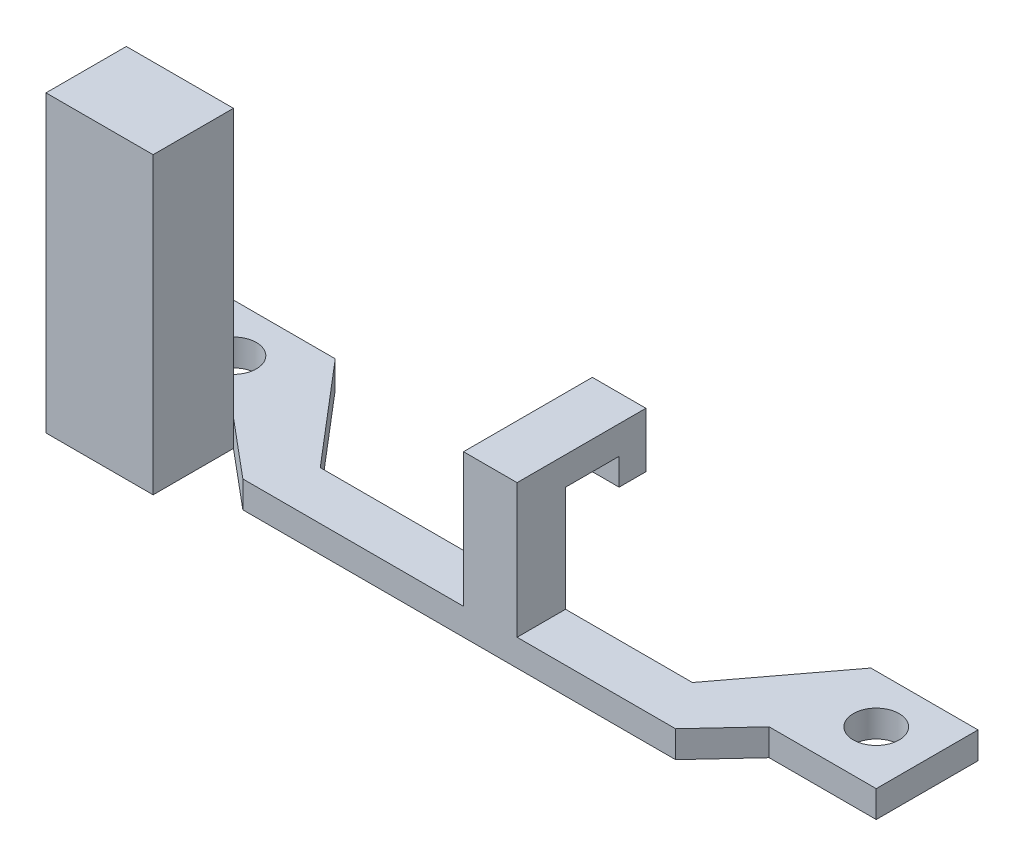
SolidWorks part; units mm, degrees
ref_plane "Front Plane" through (0, 0, 0) normal (0, 0, 1) x (1, 0, 0)
ref_plane "Top Plane" through (0, 0, 0) normal (0, 1, 0) x (1, 0, 0)
ref_plane "Right Plane" through (0, 0, 0) normal (1, 0, 0) x (0, 0, -1)
sketch "Sketch1" plane through (0, 0, 0) normal (0, 1, 0) x (1, 0, 0)
  line L2 (0, -5.08) -> (-5.08, -5.08)
  line L3 (-5.08, -5.08) -> (-5.08, 4.572)
  line L4 (-5.08, 4.572) -> (5.08, 4.572)
  line L6 (5.08, -5.08) -> (0, -5.08)
  line L7 (5.08, -5.08) -> (10.5677, -9.6777)
  line L8 (10.5677, -9.6777) -> (51.6061, -9.6777)
  line L10 (60.96, -5.08) -> (66.04, -5.08)
  line L11 (66.04, -5.08) -> (66.04, 4.572)
  line L12 (66.04, 4.572) -> (55.88, 4.572)
  line L14 (55.88, -5.08) -> (60.96, -5.08)
  line L15 (5.08, 4.572) -> (13.3093, -5.08)
  line L16 (55.88, -5.08) -> (51.6061, -9.6777)
  line L17 (13.3093, -5.08) -> (48.6075, -5.08)
  line L18 (48.6075, -5.08) -> (55.88, 4.572)
  circle A0 centre (0, 0) radius 2.1717
  circle A1 centre (60.96, 0) radius 2.1717
extrude "Boss-Extrude1" add sketch "Sketch1" along normal blind 2.54
sketch "Sketch2" plane through (0, 2.54, 0) normal (0, 1, 0) x (1, 0, 0)
  line L0 (-5.08, -5.08) -> (-5.08, -12.7)
  line L1 (-5.08, -12.7) -> (5.08, -12.7)
  line L2 (5.08, -12.7) -> (5.08, -5.08)
  line L3 (5.08, -5.08) -> (-5.08, -5.08)
extrude "Boss-Extrude2" add sketch "Sketch2" along normal blind 25.4 and the other way blind 2.54
sketch "Sketch3" plane through (0, 2.54, 0) normal (0, 1, 0) x (1, 0, 0)
  line L3 (48.6075, -5.08) -> (13.3093, -5.08) construction
  line L4 (31.496, -5.08) -> (31.496, -9.6777)
  line L5 (10.5677, -9.6777) -> (51.6061, -9.6777) construction
  line L6 (31.496, -9.6777) -> (36.576, -9.6777)
  line L7 (31.496, -5.08) -> (36.576, -5.08)
  line L8 (36.576, -5.08) -> (36.576, -9.6777)
extrude "Boss-Extrude3" add sketch "Sketch3" along normal blind 12.7
sketch "Sketch4" plane through (36.576, 0, 0) normal (1, 0, 0) x (0, 0, -1)
  line L0 (-5.08, 15.24) -> (2.54, 15.24)
  line L1 (2.54, 15.24) -> (2.54, 10.0262)
  line L2 (-5.08, 15.24) -> (-5.08, 12.5662)
  line L3 (2.54, 10.0262) -> (0, 10.0262)
  line L4 (0, 10.0262) -> (0, 12.5662)
  line L5 (0, 12.5662) -> (-5.08, 12.5662)
  line L6 (-5.08, 15.24) -> (-5.08, 2.54) construction
extrude "Boss-Extrude4" add sketch "Sketch4" against normal blind 5.08
